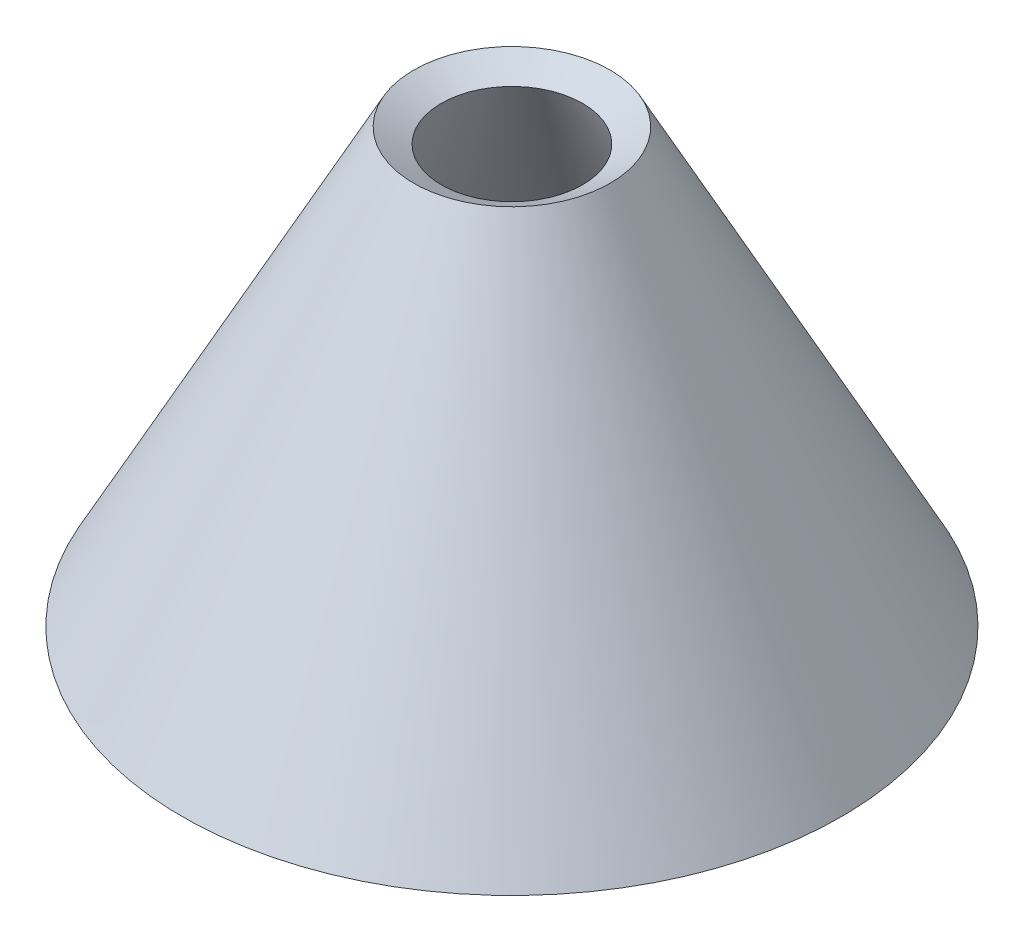
SolidWorks part; units mm, degrees
material "PF"
ref_plane "Plan de face" through (0, 0, 0) normal (0, 0, 1) x (1, 0, 0)
ref_plane "Plan de dessus" through (0, 0, 0) normal (0, 1, 0) x (1, 0, 0)
ref_plane "Plan de droite" through (0, 0, 0) normal (1, 0, 0) x (0, 0, -1)
sketch "Esquisse1" plane through (0, 0, 0) normal (0, 0, 1) x (1, 0, 0)
  line L0 (0, 15.4718) -> (0, -19.9702) construction
  line L1 (-4.5, 13.5634) -> (-19.2318, -13.9906)
  line L2 (-19.2318, -13.9906) -> (-20.9954, -13.0477)
  line L3 (-20.9954, -13.0477) -> (-6.2537, 14.5249)
  line L4 (-6.2537, 14.5249) -> (-4.5, 13.5634)
  dimension "D1" = 4.5
  dimension "D2" = 2
revolve "Révolution1" add sketch "Esquisse1" angle 360 about L0
